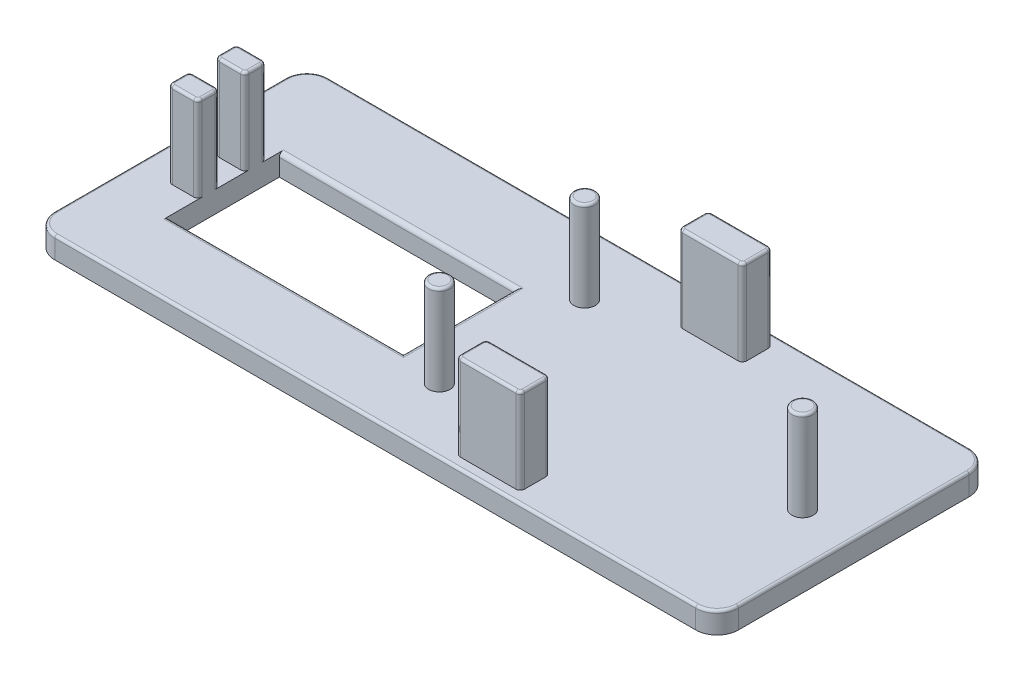
SolidWorks part; units mm, degrees
ref_plane "Front Plane" through (0, 0, 0) normal (0, 0, 1) x (1, 0, 0)
ref_plane "Top Plane" through (0, 0, 0) normal (0, 1, 0) x (1, 0, 0)
ref_plane "Right Plane" through (0, 0, 0) normal (1, 0, 0) x (0, 0, -1)
sketch "Sketch3" plane through (0, 0, 0) normal (0, 1, 0) x (1, 0, 0)
  line L0 (-38.5, -16) -> (-38.5, 16)
  line L1 (-31, -11) -> (31, -11)
  line L2 (-31, -11) -> (-31, 11)
  line L3 (-31, 11) -> (31, 11)
  line L4 (31, -11) -> (31, 11)
  line L5 (-31, -11) -> (31, 11) construction
  line L6 (-31, 11) -> (31, -11) construction
  line L7 (-36, 18.5) -> (36, 18.5)
  line L8 (38.5, -16) -> (38.5, 16)
  line L9 (-36, -18.5) -> (36, -18.5)
  line L10 (-38.5, -18.5) -> (-38.5, 18.5) construction
  line L11 (-38.5, -18.5) -> (38.5, -18.5) construction
  line L12 (38.5, -18.5) -> (38.5, 18.5) construction
  line L13 (-38.5, 18.5) -> (38.5, 18.5) construction
  line L14 (0, 0) -> (34, 0) construction
  line L15 (0, -8.5) -> (0, 8.5) construction
  arc A0 (-38.5, -16) -> (-36, -18.5) centre (-36, -16) ccw
  arc A1 (38.5, -16) -> (36, -18.5) centre (36, -16) cw
  arc A2 (36, 18.5) -> (38.5, 16) centre (36, 16) cw
  arc A3 (-38.5, 16) -> (-36, 18.5) centre (-36, 16) cw
  circle A4 centre (0, 8.5) radius 1.25
  circle A5 centre (0, -8.5) radius 1.25
  circle A6 centre (34, 0) radius 1.25
  point P0 (0, 0)
  point P27 (0, 0)
  dimension "D4" = 2.5
  dimension "D6" = 2.5
  dimension "D1" = 62
  dimension "D2" = 22
  dimension "D5" = 17
  dimension "D7" = 34
  dimension "D3" = 7.5
extrude "Boss-Extrude1" add sketch "Sketch3" along normal blind 10.5 contours A4 | A5 | A6
sketch "Sketch7" plane through (0, 0, 0) normal (0, 1, 0) x (1, 0, 0)
  line L0 (0, 0) -> (50000, 0) construction
  line L1 (-37.5, -16) -> (37.5, -16)
  line L2 (-40, -13.5) -> (-40, 13.5)
  line L3 (-37.5, 16) -> (37.5, 16)
  line L4 (40, -13.5) -> (40, 13.5)
  line L5 (-40, -16) -> (40, 16) construction
  line L6 (-40, 16) -> (40, -16) construction
  line L7 (-34.5, -11) -> (34.5, -11)
  line L8 (-34.5, -11) -> (-34.5, 11)
  line L9 (-34.5, 11) -> (34.5, 11)
  line L10 (34.5, -11) -> (34.5, 11)
  line L11 (-34.5, -11) -> (34.5, 11) construction
  line L12 (-34.5, 11) -> (34.5, -11) construction
  line L13 (8.7135, -11.254) -> (15.2135, -11.254)
  line L14 (8.2135, -11.754) -> (8.2135, -14.254)
  line L15 (8.7135, -14.754) -> (15.2135, -14.754)
  line L16 (15.7135, -11.754) -> (15.7135, -14.254)
  line L17 (8.7135, 14.754) -> (15.2135, 14.754)
  line L18 (15.7135, 11.754) -> (15.7135, 14.254)
  line L19 (8.7135, 11.254) -> (15.2135, 11.254)
  line L20 (8.2135, 11.754) -> (8.2135, 14.254)
  line L21 (-36.254, -3.5) -> (-36.254, -2)
  line L22 (-35.754, 4) -> (-33.254, 4)
  line L23 (-36.254, 3.5) -> (-36.254, 2)
  line L24 (-35.754, 1.5) -> (-33.254, 1.5)
  line L25 (-32.754, 3.5) -> (-32.754, 2)
  line L26 (-35.754, -4) -> (-33.254, -4)
  line L27 (-32.754, -3.5) -> (-32.754, -2)
  line L28 (-35.754, -1.5) -> (-33.254, -1.5)
  line L29 (-32.5, -2.7787) -> (-32.5, 2.7787) construction
  arc A0 (-37.5, -16) -> (-40, -13.5) centre (-37.5, -13.5) cw
  arc A1 (37.5, -16) -> (40, -13.5) centre (37.5, -13.5) ccw
  arc A2 (37.5, 16) -> (40, 13.5) centre (37.5, 13.5) cw
  arc A3 (-40, 13.5) -> (-37.5, 16) centre (-37.5, 13.5) cw
  arc A4 (8.2135, -14.254) -> (8.7135, -14.754) centre (8.7135, -14.254) ccw
  arc A5 (15.2135, -14.754) -> (15.7135, -14.254) centre (15.2135, -14.254) ccw
  arc A6 (15.2135, -11.254) -> (15.7135, -11.754) centre (15.2135, -11.754) cw
  arc A7 (8.7135, -11.254) -> (8.2135, -11.754) centre (8.7135, -11.754) ccw
  arc A8 (8.7135, 14.754) -> (8.2135, 14.254) centre (8.7135, 14.254) ccw
  arc A9 (15.2135, 14.754) -> (15.7135, 14.254) centre (15.2135, 14.254) cw
  arc A10 (15.7135, 11.754) -> (15.2135, 11.254) centre (15.2135, 11.754) cw
  arc A11 (8.7135, 11.254) -> (8.2135, 11.754) centre (8.7135, 11.754) cw
  arc A12 (-35.754, 4) -> (-36.254, 3.5) centre (-35.754, 3.5) ccw
  arc A13 (-36.254, 2) -> (-35.754, 1.5) centre (-35.754, 2) ccw
  arc A14 (-36.254, -2) -> (-35.754, -1.5) centre (-35.754, -2) cw
  arc A15 (-36.254, -3.5) -> (-35.754, -4) centre (-35.754, -3.5) ccw
  arc A16 (-33.254, -4) -> (-32.754, -3.5) centre (-33.254, -3.5) ccw
  arc A17 (-32.754, -2) -> (-33.254, -1.5) centre (-33.254, -2) ccw
  arc A18 (-33.254, 4) -> (-32.754, 3.5) centre (-33.254, 3.5) cw
  arc A19 (-33.254, 1.5) -> (-32.754, 2) centre (-33.254, 2) ccw
  point P0 (0, 0)
  point P18 (0, 0)
  point P35 (8.2135, -14.754)
  point P38 (15.7135, -14.754)
  point P41 (15.7135, -11.254)
  point P44 (8.2135, -11.254)
  point P47 (8.2135, 14.754)
  point P50 (15.7135, 14.754)
  point P53 (15.7135, 11.254)
  point P56 (8.2135, 11.254)
  point P67 (-36.254, 4)
  point P70 (-36.254, 1.5)
  point P73 (-36.254, -1.5)
  point P76 (-36.254, -4)
  point P79 (-32.754, -4)
  point P82 (-32.754, -1.5)
  point P85 (-32.754, 4)
  point P88 (-32.754, 1.5)
  point P89 (-32.754, 2.75)
  dimension "D3" = 2.5
  dimension "D9" = 0.5
  dimension "D14" = 0.5
  dimension "D1" = 80
  dimension "D2" = 32
  dimension "D4" = 22
  dimension "D5" = 69
  dimension "D6" = 7.5
  dimension "D7" = 3.5
  dimension "D8" = 0.254
  dimension "D10" = 3
  dimension "D11" = 2.5
  dimension "D12" = 3.5
  dimension "D13" = 0.254
extrude "Boss-Extrude2" add sketch "Sketch7" along normal blind 10 contours L14 A4 L15 A5 L16 A6 L13 A7 | A9 L18 A10 L19 A11 L20 A8 L17 | A18 L25 A19 L24 A13 L23 A12 L22 | A17 L28 A14 L21 A15 L26 A16 L27
sketch "Sketch8" plane through (0, 0, 0) normal (0, 1, 0) x (1, 0, 0)
  line L1 (-37.5, -16) -> (37.5, -16)
  line L2 (-40, -13.5) -> (-40, 13.5)
  line L3 (-37.5, 16) -> (37.5, 16)
  line L4 (40, -13.5) -> (40, 13.5)
  line L5 (-40, -16) -> (40, 16) construction
  line L6 (-40, 16) -> (40, -16) construction
  arc A0 (-37.5, -16) -> (-40, -13.5) centre (-37.5, -13.5) cw
  arc A1 (37.5, -16) -> (40, -13.5) centre (37.5, -13.5) ccw
  arc A2 (37.5, 16) -> (40, 13.5) centre (37.5, 13.5) cw
  arc A3 (-40, 13.5) -> (-37.5, 16) centre (-37.5, 13.5) cw
  point P0 (0, 0)
  dimension "D3" = 2.5
  dimension "D1" = 80
  dimension "D2" = 32
extrude "Boss-Extrude3" add sketch "Sketch8" against normal blind 2.5
fillet "Fillet1" radius 0.3 43 edges at (34, 10.5, 1.25) (0, 10.5, 9.75) (0, 10.5, -7.25) (-32.9004, 10, -3.8536) (-32.754, 10, -2.75) (-32.9004, 10, -1.6464) (-34.504, 10, -1.5) (-36.1076, 10, -1.6464) (-36.254, 10, -2.75) (-36.1076, 10, -3.8536) (-34.504, 10, -4) (-32.9004, 10, 3.8536) (-34.504, 10, 4) (-36.1076, 10, 3.8536) (-36.254, 10, 2.75) (-36.1076, 10, 1.6464) (-34.504, 10, 1.5) (-32.9004, 10, 1.6464) (-32.754, 10, 2.75) (11.9635, 10, 11.254) (15.5671, 10, 11.4004) (15.7135, 10, 13.004) (15.5671, 10, 14.6076) (11.9635, 10, 14.754) (8.36, 10, 14.6076) (8.2135, 10, 13.004) (8.36, 10, 11.4004) (15.5671, 10, -14.6076) (15.7135, 10, -13.004) (15.5671, 10, -11.4004) (11.9635, 10, -11.254) (8.36, 10, -11.4004) (8.2135, 10, -13.004) (8.36, 10, -14.6076) (11.9635, 10, -14.754) (-40, 0, 0) (-39.2678, 0, -15.2678) (0, 0, -16) (39.2678, 0, -15.2678) (40, 0, 0) (39.2678, 0, 15.2678) (0, 0, 16) (-39.2678, 0, 15.2678)
sketch "Sketch9" plane through (0, 0, 0) normal (0, 1, 0) x (1, 0, 0)
  line L0 (-32.754, -3.5) -> (-32.754, -2) construction
  line L1 (-32.754, 5.5244) -> (-5.2179, 5.5244)
  line L2 (-32.754, 5.5244) -> (-32.754, -7.4756)
  line L3 (-32.754, -7.4756) -> (-5.2179, -7.4756)
  line L4 (-5.2179, 5.5244) -> (-5.2179, -7.4756)
  dimension "D1" = 13
extrude "Cut-Extrude1" cut sketch "Sketch9" against normal through all
fillet "Fillet2" radius 0.5 3 edges at (-18.9859, 0, 7.4756) (-5.2179, 0, 0.9756) (-18.9859, 0, -5.5244)
